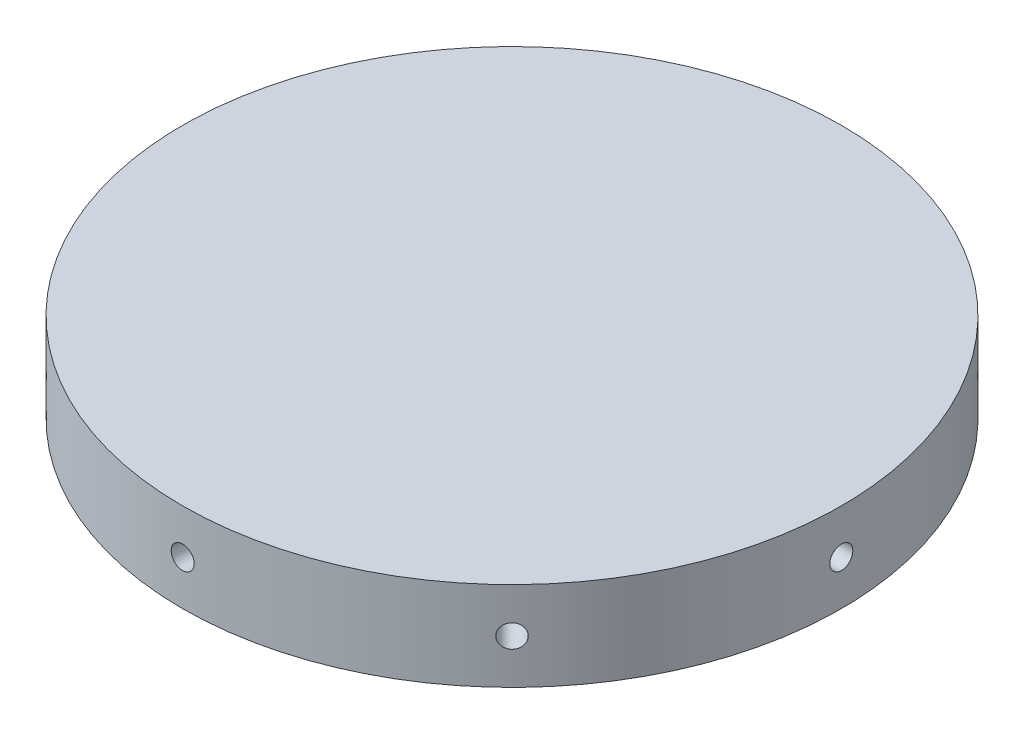
SolidWorks part; units mm, degrees
material "6061 Alloy"
ref_plane "Front Plane" through (0, 0, 0) normal (0, 0, 1) x (1, 0, 0)
ref_plane "Top Plane" through (0, 0, 0) normal (0, 1, 0) x (1, 0, 0)
ref_plane "Right Plane" through (0, 0, 0) normal (1, 0, 0) x (0, 0, -1)
sketch "Sketch1" plane through (0, 0, 0) normal (0, 1, 0) x (1, 0, 0)
  circle A0 centre (0, 0) radius 46.99
  dimension "D1" = 93.98
extrude "Bulkhead Extrusion" add sketch "Sketch1" along normal blind 12.7
ref_plane "Plane1" through (0, 0, 46.99) normal (0, 0, 1) x (1, 0, 0)
sketch "Sketch2" plane through (0, 0, 46.99) normal (0, 0, 1) x (1, 0, 0)
  line L0 (0, 12.7) -> (0, 0) construction
  line L1 (46.99, 12.7) -> (-46.99, 12.7) construction
  circle A0 centre (0, 6.35) radius 1.6383
  dimension "D1" = 3.2766
extrude "Screw Hole" cut sketch "Sketch2" against normal blind 12.7
pattern_circular "CirPattern1" count 8 over 360 about axis through (0, 0, 0) along (0, 1, 0) of "Screw Hole"
